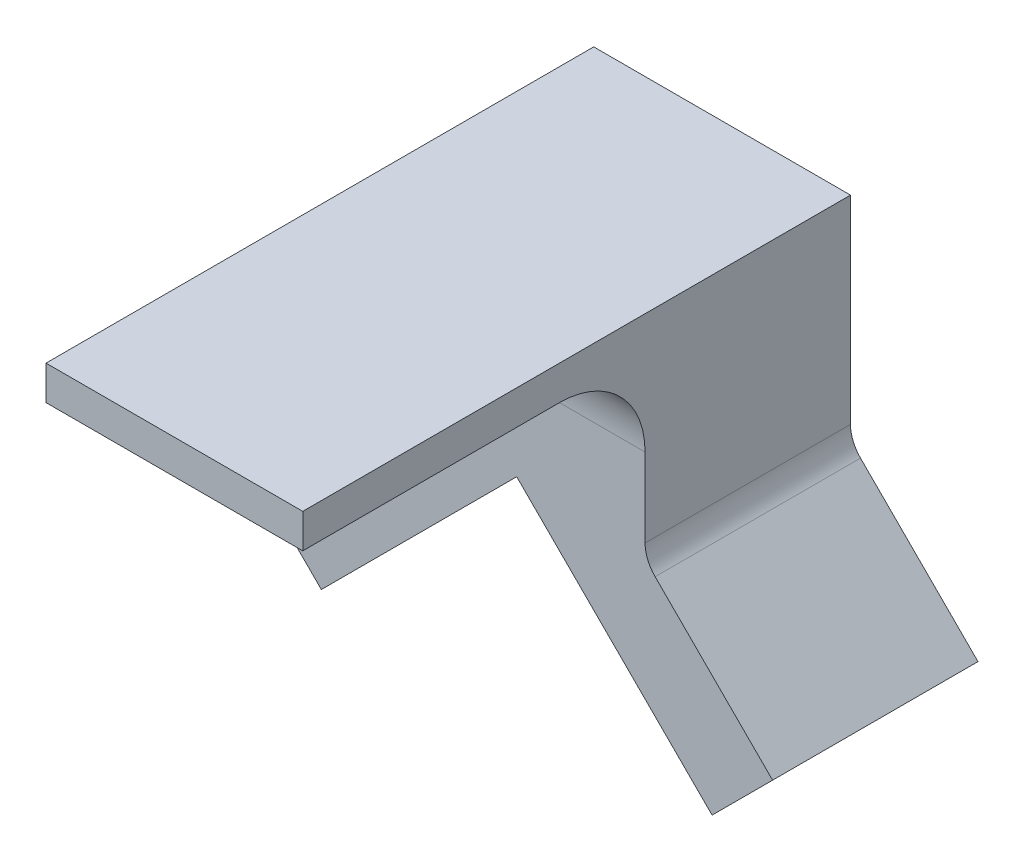
SolidWorks part; units mm, degrees
ref_plane "Plan de face" through (0, 0, 0) normal (0, 0, 1) x (1, 0, 0)
ref_plane "Plan de dessus" through (0, 0, 0) normal (0, 1, 0) x (1, 0, 0)
ref_plane "Plan de droite" through (0, 0, 0) normal (1, 0, 0) x (0, 0, -1)
sketch "Esquisse2" plane through (0, 0, 0) normal (0, 0, 1) x (1, 0, 0)
  line L19 (7.5, 0) -> (7.5, -20)
  line L24 (0, 0) -> (15, 0)
  line L25 (0, 0) -> (0, -20)
  line L26 (0, -20) -> (15, -20)
  line L27 (15, 0) -> (15, -20)
  line L28 (7.5, -10) -> (-2.5, -20)
  line L29 (-2.5, -20) -> (-6.0355, -16.4645)
  line L30 (-6.0355, -16.4645) -> (0, -10.4289)
  line L31 (0, -10.4289) -> (0, 0)
  line L32 (7.5, -10) -> (17.5, -20)
  line L33 (17.5, -20) -> (21.0355, -16.4645)
  line L34 (21.0355, -16.4645) -> (15, -10.4289)
  line L35 (15, -10.4289) -> (15, 0)
  line L36 (-6.0355, -16.4645) -> (-7.4497, -17.8787)
  line L37 (-2.5, -20) -> (-3.9142, -21.4142)
  line L38 (-3.9142, -21.4142) -> (-7.4497, -17.8787)
  line L39 (-6.0355, -16.4645) -> (-2.5, -20)
  line L40 (21.0355, -16.4645) -> (22.4497, -17.8787)
  line L42 (17.5, -20) -> (18.9142, -21.4142)
  line L43 (18.9142, -21.4142) -> (22.4497, -17.8787)
  dimension "D1" = 20
  dimension "D2" = 15
  dimension "D3" = 5
  dimension "D4" = 5
  dimension "D5" = 90
  dimension "D6" = 2
  dimension "D7" = 2
extrude "Boss.-Extru.1" add sketch "Esquisse2" along normal blind 12 contours L30 L29 L28 L25 | L28 L19 L24 L25 | L19 L32 L27 L24 | L33 L34 L27 L32 | L38 L37 L29 L36 | L42 L43 L40 L33
sketch "Esquisse3" plane through (0, 0, 0) normal (0, 1, 0) x (1, 0, 0)
  line L1 (0, 0) -> (15, 0)
  line L2 (0, 0) -> (0, -32)
  line L3 (0, -32) -> (15, -32)
  line L4 (15, 0) -> (15, -32)
  dimension "D1" = 15
  dimension "D2" = 32
extrude "Boss.-Extru.2" add sketch "Esquisse3" along normal blind 2
fillet "Congé2" radius 2 2 edges at (0, -10.4289, 6) (15, -10.4289, 6)
fillet "Congé3" radius 5 1 edges at (7.5, 0, 12)
